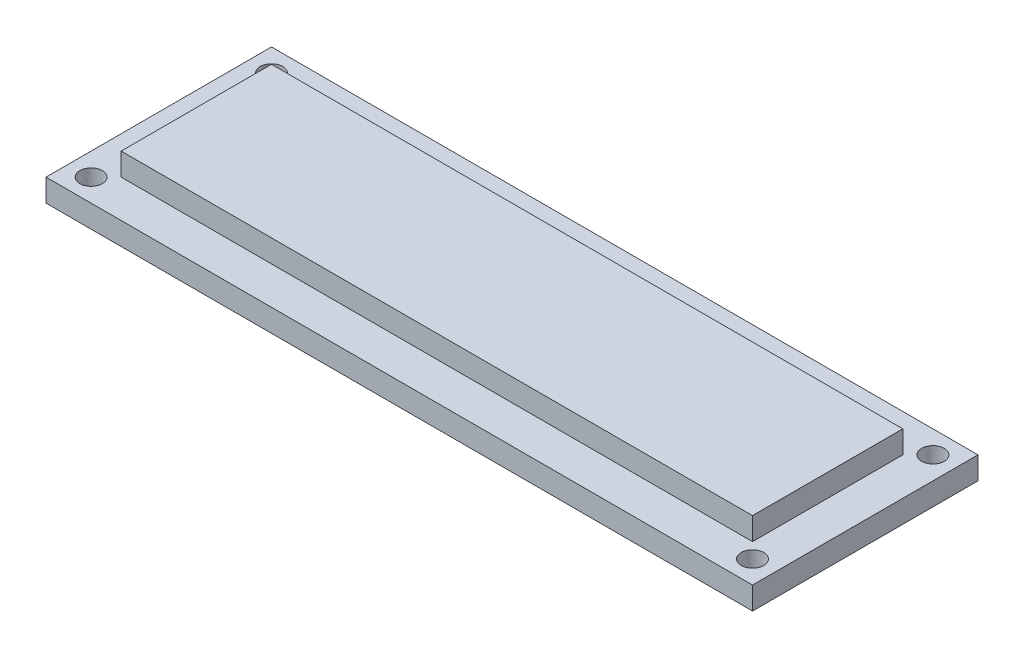
SolidWorks part; units mm, degrees
ref_plane "Front Plane" through (0, 0, 0) normal (0, 0, 1) x (1, 0, 0)
ref_plane "Top Plane" through (0, 0, 0) normal (0, 1, 0) x (1, 0, 0)
ref_plane "Right Plane" through (0, 0, 0) normal (1, 0, 0) x (0, 0, -1)
sketch "Sketch1" plane through (0, 0, 0) normal (0, 1, 0) x (1, 0, 0)
  line L1 (-42, -10) -> (42, -10)
  line L2 (-42, -10) -> (-42, 10)
  line L3 (-42, 10) -> (42, 10)
  line L4 (42, -10) -> (42, 10)
  line L5 (-42, -10) -> (42, 10) construction
  line L6 (-42, 10) -> (42, -10) construction
  point P0 (0, 0)
  dimension "D1" = 84
  dimension "D2" = 20
extrude "Boss-Extrude1" add sketch "Sketch1" along normal blind 3
sketch "Sketch2" plane through (0, 0, 0) normal (0, -1, 0) x (1, 0, 0)
  line L5 (44, -12) -> (-44, -12) construction
  line L6 (44, -12) -> (44, 12) construction
  line L7 (44, 12) -> (-44, 12) construction
  line L8 (47, -15) -> (47, 15)
  line L9 (47, 15) -> (-47, 15)
  line L10 (-47, 15) -> (-47, -15)
  line L11 (-47, -15) -> (47, -15)
  line L12 (47, -15) -> (47, 15)
  line L13 (47, 15) -> (-47, 15)
  line L14 (-47, 15) -> (-47, -15)
  line L15 (-47, -15) -> (47, -15)
  line L16 (-44, -12) -> (-44, 12) construction
  line L17 (44, -12) -> (-44, 12) construction
  line L18 (44, 12) -> (-44, -12) construction
  circle A0 centre (-44, 12) radius 1.5
  circle A1 centre (-44, -12) radius 1.5
  circle A2 centre (44, 12) radius 1.5
  circle A3 centre (44, -12) radius 1.5
  point P0 (0, 0)
  dimension "D2" = 3
  dimension "D3" = 3
  dimension "D4" = 3
  dimension "D1" = 5
extrude "Boss-Extrude2" add sketch "Sketch2" along normal blind 3
